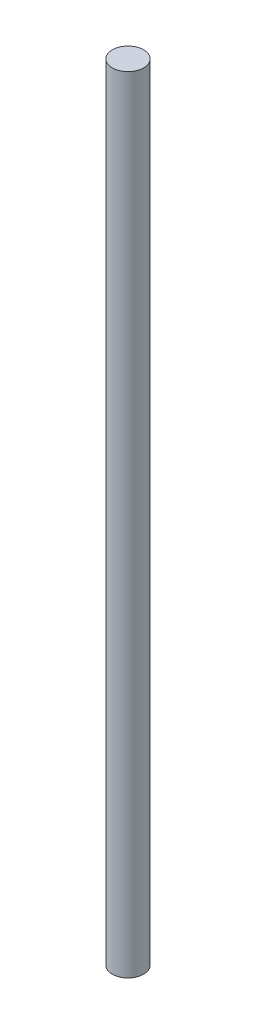
SolidWorks part; units mm, degrees
ref_plane "Front Plane" through (0, 0, 0) normal (0, 0, 1) x (1, 0, 0)
ref_plane "Top Plane" through (0, 0, 0) normal (0, 1, 0) x (1, 0, 0)
ref_plane "Right Plane" through (0, 0, 0) normal (1, 0, 0) x (0, 0, -1)
sketch "Sketch1" plane through (0, 0, 0) normal (0, 1, 0) x (1, 0, 0)
  circle A0 centre (0, 0) radius 200
  dimension "D1" = 400
extrude "Boss-Extrude1" add sketch "Sketch1" along normal blind 10000
